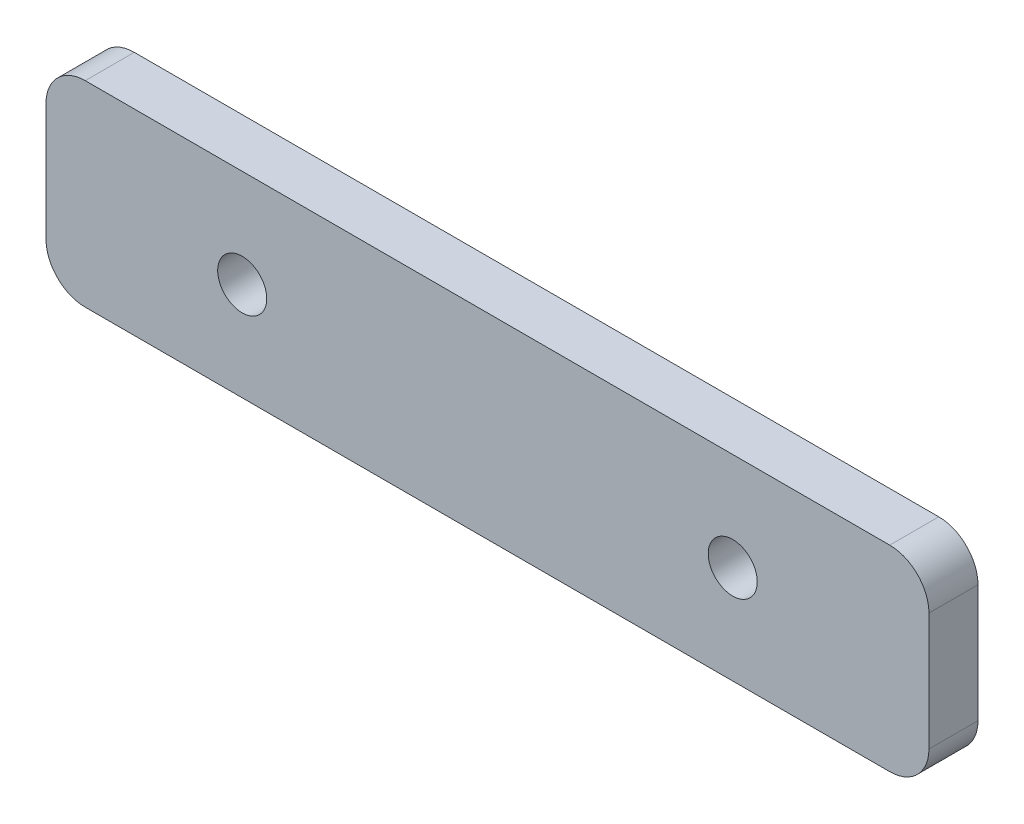
SolidWorks part; units mm, degrees
material "6061 Alloy"
ref_plane "Front Plane" through (0, 0, 0) normal (0, 0, 1) x (1, 0, 0)
ref_plane "Top Plane" through (0, 0, 0) normal (0, 1, 0) x (1, 0, 0)
ref_plane "Right Plane" through (0, 0, 0) normal (1, 0, 0) x (0, 0, -1)
sketch "Sketch1" plane through (0, 0, 0) normal (0, 0, 1) x (1, 0, 0)
  line L1 (-28.575, -6.35) -> (28.575, -6.35)
  line L2 (-28.575, -6.35) -> (-28.575, 6.35)
  line L3 (-28.575, 6.35) -> (28.575, 6.35)
  line L4 (28.575, -6.35) -> (28.575, 6.35)
  line L5 (-28.575, -6.35) -> (28.575, 6.35) construction
  line L6 (-28.575, 6.35) -> (28.575, -6.35) construction
  circle A0 centre (-15.875, 0) radius 1.5875
  circle A1 centre (15.875, 0) radius 1.5875
  point P0 (0, 0)
  point P7 (-28.575, 0)
  point P12 (28.575, 0)
  dimension "D3" = 3.175
  dimension "D4" = 3.175
  dimension "D6" = 12.7
  dimension "D1" = 12.7
  dimension "D2" = 57.15
  dimension "D5" = 12.7
extrude "Boss-Extrude1" add sketch "Sketch1" along normal blind 3.175
fillet "Fillet1" radius 2.54 4 edges at (28.575, -6.35, 1.5875) (-28.575, -6.35, 1.5875) (28.575, 6.35, 1.5875) (-28.575, 6.35, 1.5875)
